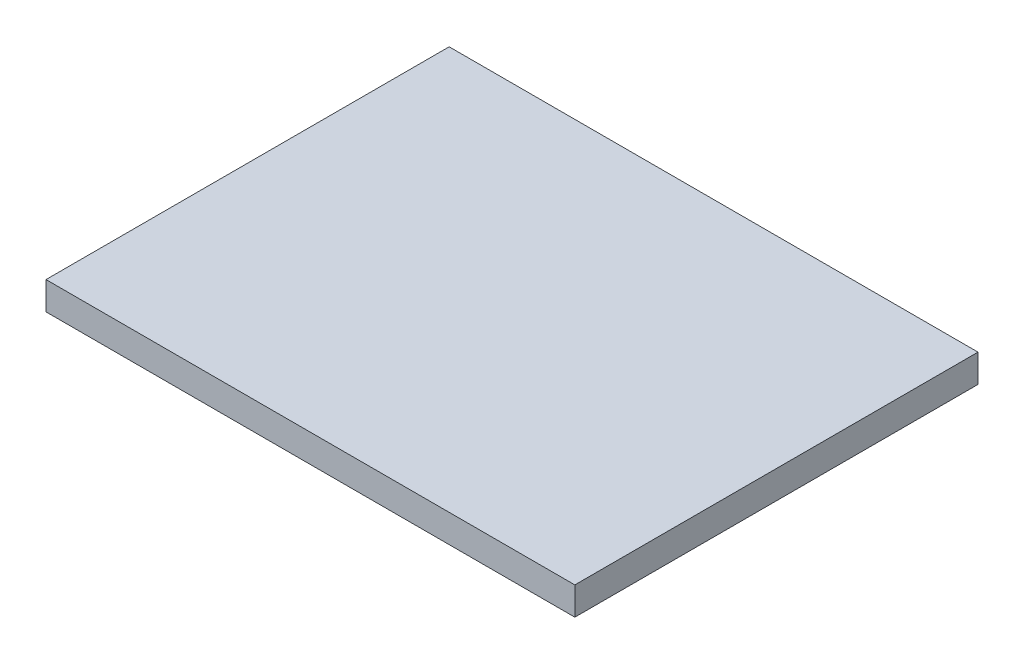
SolidWorks part; units mm, degrees
ref_plane "Front Plane" through (0, 0, 0) normal (0, 0, 1) x (1, 0, 0)
ref_plane "Top Plane" through (0, 0, 0) normal (0, 1, 0) x (1, 0, 0)
ref_plane "Right Plane" through (0, 0, 0) normal (1, 0, 0) x (0, 0, -1)
sketch "Sketch1" plane through (0, 0, 0) normal (0, 1, 0) x (1, 0, 0)
  line L1 (-22.5842, -17.2529) -> (25.398, -17.2529)
  line L2 (-22.5842, -17.2529) -> (-22.5842, 19.3262)
  line L3 (-22.5842, 19.3262) -> (25.398, 19.3262)
  line L4 (25.398, -17.2529) -> (25.398, 19.3262)
extrude "Boss-Extrude1" add sketch "Sketch1" along normal blind 2.54
